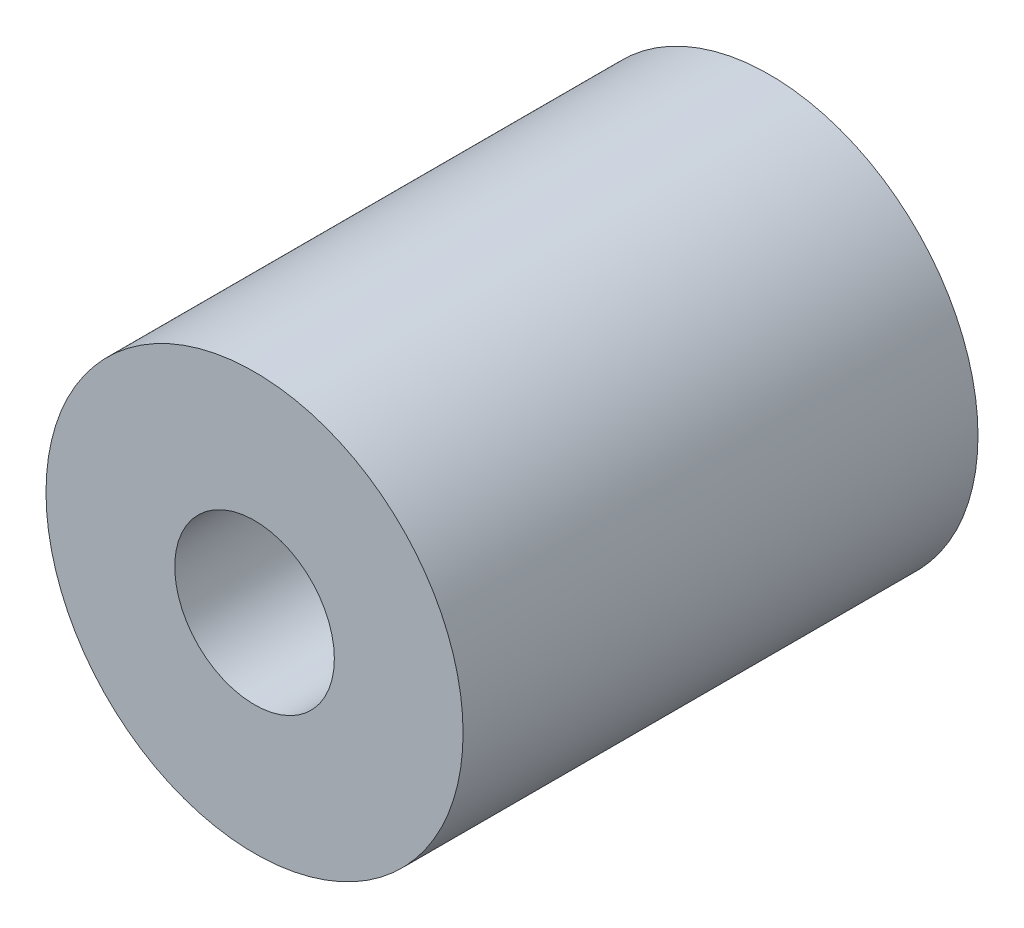
SolidWorks part; units mm, degrees
ref_plane "前视基准面" through (0, 0, 0) normal (0, 0, 1) x (1, 0, 0)
ref_plane "上视基准面" through (0, 0, 0) normal (0, 1, 0) x (1, 0, 0)
ref_plane "右视基准面" through (0, 0, 0) normal (1, 0, 0) x (0, 0, -1)
other "Configuration Table"
sketch "草图1" plane through (0, 0, 0) normal (0, 0, 1) x (1, 0, 0)
  circle A0 centre (0, 0) radius 1.55
  dimension "D1" = 3.1
extrude "拉伸-薄壁1" add sketch "草图1" along normal blind 10 thin
